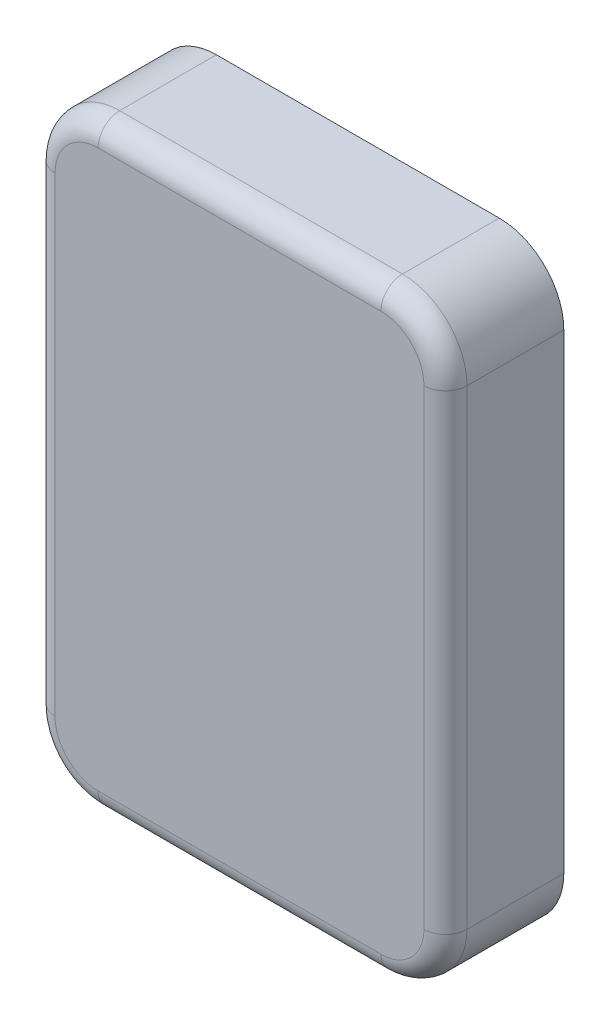
SolidWorks part; units mm, degrees
ref_plane "Front Plane" through (0, 0, 0) normal (0, 0, 1) x (1, 0, 0)
ref_plane "Top Plane" through (0, 0, 0) normal (0, 1, 0) x (1, 0, 0)
ref_plane "Right Plane" through (0, 0, 0) normal (1, 0, 0) x (0, 0, -1)
sketch "Sketch1" plane through (0, 0, 0) normal (0, 0, 1) x (1, 0, 0)
  line L0 (-0.5, 27.54) -> (-0.5, 0.5) construction
  line L2 (34.79, 0.5) -> (34.79, 44.26) construction
  line L4 (-0.5, 44.26) -> (-0.5, 35.94) construction
  line L5 (-0.5, 27.44) -> (-0.5, 0.5)
  line L7 (34.79, 0.5) -> (34.79, 44.26)
  line L8 (30.29, 48.76) -> (4, 48.76)
  line L9 (-0.5, 44.26) -> (-0.5, 36.04)
  line L10 (-2, 27.54) -> (-2, 0.5) construction
  line L12 (36.29, 0.5) -> (36.29, 44.26) construction
  line L14 (-2, 44.26) -> (-2, 35.94) construction
  line L15 (-2, 27.44) -> (-2, 0.5)
  line L17 (36.29, 0.5) -> (36.29, 44.26)
  line L18 (30.29, 50.26) -> (4, 50.26)
  line L19 (-2, 44.26) -> (-2, 36.04)
  line L22 (-2, 27.44) -> (-0.5, 27.44)
  line L23 (-2, 36.04) -> (-0.5, 36.04)
  line L24 (-0.5, 35.94) -> (-2, 35.94) construction
  line L25 (-2, 27.54) -> (-0.5, 27.54) construction
  line L26 (34.79, 22.38) -> (7.5344, 22.38) construction
  line L32 (30.29, -5.5) -> (4, -5.5)
  line L33 (30.29, -4) -> (4, -4)
  arc A1 (34.79, 0.5) -> (30.29, -4) centre (30.29, 0.5) cw
  arc A2 (34.79, 44.26) -> (30.29, 48.76) centre (30.29, 44.26) ccw construction
  arc A3 (4, 48.76) -> (-0.5, 44.26) centre (4, 44.26) ccw construction
  arc A6 (34.79, 44.26) -> (30.29, 48.76) centre (30.29, 44.26) ccw
  arc A7 (4, 48.76) -> (-0.5, 44.26) centre (4, 44.26) ccw
  arc A8 (36.29, 0.5) -> (30.29, -5.5) centre (30.29, 0.5) cw
  arc A10 (36.29, 44.26) -> (30.29, 50.26) centre (30.29, 44.26) ccw construction
  arc A11 (4, 50.26) -> (-2, 44.26) centre (4, 44.26) ccw construction
  arc A14 (36.29, 44.26) -> (30.29, 50.26) centre (30.29, 44.26) ccw
  arc A15 (4, 50.26) -> (-2, 44.26) centre (4, 44.26) ccw
  arc A16 (4, -4) -> (-0.5, 0.5) centre (4, 0.5) cw
  arc A17 (4, -5.5) -> (-2, 0.5) centre (4, 0.5) cw
  dimension "D1" = 0.1
  dimension "D2" = 0.1
extrude "Boss-Extrude1" add sketch "Sketch1" along normal blind 8
sketch "Sketch12" plane through (0, 0, 8) normal (0, 0, 1) x (1, 0, 0)
  line L0 (-2, 36.04) -> (-0.5, 36.04)
  line L1 (-0.5, 36.04) -> (-0.5, 27.44)
  line L2 (-0.5, 27.44) -> (-2, 27.44)
  line L3 (-2, 27.44) -> (-2, 36.04)
extrude "Boss-Extrude8" add sketch "Sketch12" against normal blind 3
sketch "Sketch8" plane through (0, 0, 8) normal (0, 0, 1) x (1, 0, 0)
  line L10 (-2, 44.26) -> (-2, 0.5) construction
  line L11 (30.29, -5.5) -> (4, -5.5) construction
  line L12 (36.29, 0.5) -> (36.29, 44.26) construction
  line L13 (30.29, 50.26) -> (4, 50.26) construction
  line L14 (-2, 44.26) -> (-2, 0.5)
  line L15 (30.29, -5.5) -> (4, -5.5)
  line L16 (36.29, 0.5) -> (36.29, 44.26)
  line L17 (30.29, 50.26) -> (4, 50.26)
  arc A8 (-2, 0.5) -> (4, -5.5) centre (4, 0.5) ccw construction
  arc A9 (30.29, -5.5) -> (36.29, 0.5) centre (30.29, 0.5) ccw construction
  arc A10 (36.29, 44.26) -> (30.29, 50.26) centre (30.29, 44.26) ccw construction
  arc A11 (4, 50.26) -> (-2, 44.26) centre (4, 44.26) ccw construction
  arc A12 (-2, 0.5) -> (4, -5.5) centre (4, 0.5) ccw
  arc A13 (30.29, -5.5) -> (36.29, 0.5) centre (30.29, 0.5) ccw
  arc A14 (36.29, 44.26) -> (30.29, 50.26) centre (30.29, 44.26) ccw
  arc A15 (4, 50.26) -> (-2, 44.26) centre (4, 44.26) ccw
extrude "Boss-Extrude5" add sketch "Sketch8" along normal blind 3 contours A14 L17 A15 L14 A12 L15 A13 L16
sketch "Sketch10" plane through (0, 0, 8) normal (0, 0, -1) x (-1, 0, 0)
  line L4 (-30.29, 50.26) -> (-4, 50.26) construction
  line L6 (-17.145, 50.26) -> (-17.145, 41.4835) construction
  line L7 (-34.79, 22.38) -> (-17.145, 22.38) construction
  line L14 (-34.79, 0.5) -> (-34.79, 44.26) construction
  line L15 (-17.145, -5.5) -> (-17.145, 3.2765) construction
  line L16 (0.5, 44.26) -> (0.5, 36.04) construction
  line L17 (-30.29, 48.76) -> (-26.73, 48.76)
  line L18 (0.5, 44.26) -> (0.5, 40.7)
  line L19 (-3.81, 40.7) -> (0.5, 40.7)
  line L20 (-7.56, 44.45) -> (-7.56, 48.76)
  line L21 (0.5, 40.7) -> (0.5, 44.26)
  line L22 (0.5, 27.44) -> (0.5, 0.5) construction
  line L24 (0.5, 7.56) -> (0.5, 0.5)
  line L26 (-7.56, 3.81) -> (-7.56, -4)
  line L27 (-3.81, 7.56) -> (0.5, 7.56)
  line L28 (-7.56, -4) -> (-4, -4)
  line L29 (-4, 48.76) -> (-7.56, 48.76)
  line L30 (-26.73, -4) -> (-30.29, -4)
  line L31 (-30.48, 7.56) -> (-34.79, 7.56)
  line L32 (-26.73, 3.81) -> (-26.73, -4)
  line L33 (-34.79, 7.56) -> (-34.79, 0.5)
  line L34 (-34.79, 40.7) -> (-34.79, 44.26)
  line L35 (-26.73, 44.45) -> (-26.73, 48.76)
  line L36 (-30.48, 40.7) -> (-34.79, 40.7)
  line L37 (-34.79, 44.26) -> (-34.79, 40.7)
  circle A5 centre (-3.81, 44.45) radius 1.75
  arc A8 (0.5, 44.26) -> (-4, 48.76) centre (-4, 44.26) ccw construction
  arc A12 (0.5, 44.26) -> (-4, 48.76) centre (-4, 44.26) ccw
  arc A13 (-7.56, 44.45) -> (-3.81, 40.7) centre (-3.81, 44.45) ccw
  circle A14 centre (-3.81, 3.81) radius 1.75
  circle A15 centre (-3.81, 44.45) radius 3.75 construction
  arc A16 (-3.81, 7.56) -> (-7.56, 3.81) centre (-3.81, 3.81) ccw
  arc A17 (-4, -4) -> (0.5, 0.5) centre (-4, 0.5) ccw construction
  arc A18 (-4, -4) -> (0.5, 0.5) centre (-4, 0.5) ccw
  arc A19 (-30.29, -4) -> (-34.79, 0.5) centre (-30.29, 0.5) cw
  circle A20 centre (-3.81, 3.81) radius 3.75 construction
  arc A21 (-30.48, 7.56) -> (-26.73, 3.81) centre (-30.48, 3.81) cw
  circle A22 centre (-30.48, 3.81) radius 1.75
  arc A23 (-26.73, 44.45) -> (-30.48, 40.7) centre (-30.48, 44.45) cw
  arc A24 (-34.79, 44.26) -> (-30.29, 48.76) centre (-30.29, 44.26) cw
  circle A25 centre (-30.48, 44.45) radius 1.75
  point P21 (-0.0551, 44.45)
  point P39 (-0.06, 3.81)
  dimension "D2" = 3.5
  dimension "D3" = 3.5
  dimension "D1" = 2
  dimension "D4" = 2
extrude "Boss-Extrude6" add sketch "Sketch10" along normal blind 8.75 from surface at 0 starting at face at (17.145, 22.38, 8)
sketch "Sketch11" plane through (0, 0, 8) normal (0, 0, -1) x (-1, 0, 0)
  line L0 (-24.195, -4) -> (-24.195, -5.5)
  line L1 (-24.195, -5.5) -> (-10.095, -5.5)
  line L2 (-10.095, -5.5) -> (-10.095, -4)
  line L3 (-10.095, -4) -> (-24.195, -4)
  line L4 (-17.145, -5.5) -> (-17.145, -4) construction
  line L5 (-30.29, -5.5) -> (-4, -5.5) construction
  line L6 (-26.73, -4) -> (-7.56, -4) construction
  line L7 (-26.73, -4) -> (-7.56, -4) construction
  point P19 (-17.145, -5.5)
  dimension "D1" = 14.1
extrude "Boss-Extrude7" add sketch "Sketch11" along normal blind 1.5
fillet "Fillet1" radius 2 8 edges at (17.145, 50.26, 11) (34.5326, 48.5026, 11) (-0.2426, 48.5026, 11) (36.29, 22.38, 11) (34.5326, -3.7426, 11) (17.145, -5.5, 11) (-0.2426, -3.7426, 11) (-2, 22.38, 11)
sketch "Sketch13" plane through (0, -5.5, 0) normal (0, -1, 0) x (1, 0, 0)
  line L0 (17.145, 0) -> (17.145, 11) construction
  line L1 (30.29, 0) -> (4, 0) construction
  line L2 (4, 11) -> (30.29, 11) construction
  line L4 (24.145, 0) -> (10.145, 0)
  line L5 (24.145, 0) -> (24.145, 7.25)
  line L6 (24.145, 7.25) -> (10.145, 7.25)
  line L7 (10.145, 0) -> (10.145, 7.25)
  line L8 (24.145, 0) -> (10.145, 7.25) construction
  line L9 (24.145, 7.25) -> (10.145, 0) construction
  point P6 (17.145, 3.625)
  dimension "D1" = 3.75
  dimension "D2" = 14
extrude "Cut-Extrude2" cut sketch "Sketch13" against normal up to next
fillet "Fillet2" radius 1 4 edges at (24.145, -4.75, 7.25) (10.145, -4.75, 7.25) (-1.25, 27.44, 5) (-1.25, 36.04, 5)
sketch "Sketch14" plane through (0, 0, 8) normal (0, 0, -1) x (-1, 0, 0)
  line L0 (-17.145, 48.76) -> (-17.145, -4) construction
  line L1 (-26.73, 48.76) -> (-7.56, 48.76) construction
  line L2 (-11.145, -4) -> (-23.145, -4) construction
  line L4 (-11.645, -4) -> (-22.645, -4)
  line L5 (-11.645, -4) -> (-11.645, 48.76)
  line L6 (-11.645, 48.76) -> (-22.645, 48.76)
  line L7 (-22.645, -4) -> (-22.645, 48.76)
  line L8 (-11.645, -4) -> (-22.645, 48.76) construction
  line L9 (-11.645, 48.76) -> (-22.645, -4) construction
  point P6 (-17.145, 22.38)
  dimension "D1" = 11
extrude "Cut-Extrude3" cut sketch "Sketch14" against normal blind 1
sketch "Sketch15" plane through (0, 0, 9) normal (0, 0, -1) x (-1, 0, 0)
  line L0 (-22.645, 48.76) -> (-22.645, -4) construction
  line L1 (-13.145, 47.51) -> (-18.645, 47.51)
  line L2 (-13.145, 47.51) -> (-13.145, -2.75)
  line L3 (-13.145, -2.75) -> (-18.645, -2.75)
  line L4 (-18.645, 47.51) -> (-18.645, -2.75)
  line L5 (-11.145, -4) -> (-23.145, -4) construction
  line L6 (-26.73, 48.76) -> (-7.56, 48.76) construction
  dimension "D1" = 5.5
  dimension "D2" = 4
  dimension "D3" = 1.25
  dimension "D4" = 1.25
extrude "Cut-Extrude4" cut sketch "Sketch15" against normal offset from surface (1.5 mm away) 0.5 up to face at (17.145, 22.38, 11)
sketch "Sketch17" plane through (0, 0, 9) normal (0, 0, -1) x (-1, 0, 0)
  line L0 (-26.73, 48.76) -> (-7.56, 48.76) construction
  line L1 (-22.645, 48.76) -> (-22.645, -4) construction
  line L2 (-22.645, 12.36) -> (-18.645, 12.36)
  line L3 (-18.645, 47.51) -> (-18.645, -2.75) construction
  line L4 (-18.645, 12.36) -> (-18.645, 7.36)
  line L5 (-18.645, 7.36) -> (-22.645, 7.36)
  line L6 (-22.645, 7.36) -> (-22.645, 12.36)
  line L7 (-22.645, 32.76) -> (-18.645, 32.76)
  line L8 (-18.645, 32.76) -> (-18.645, 37.76)
  line L9 (-18.645, 37.76) -> (-22.645, 37.76)
  line L10 (-22.645, 37.76) -> (-22.645, 32.76)
  circle A0 centre (-20.145, 35.26) radius 1
  circle A1 centre (-20.145, 9.86) radius 1
  line M4 (-18.645, -2.75) -> (-18.645, 47.51)
  line M6 (-22.645, 48.76) -> (-22.645, -4)
  dimension "D1" = 2
  dimension "D2" = 13.5
  dimension "D3" = 2.5
  dimension "D4" = 25.4
  dimension "D5" = 2.5
  dimension "D6" = 2.5
  dimension "D7" = 2.5
  dimension "D8" = 2.5
extrude "Boss-Extrude9" add sketch "Sketch17" along normal blind 1 contours L5 L2 A1 M4 M6 | L9 L7 A0 M4 M6
